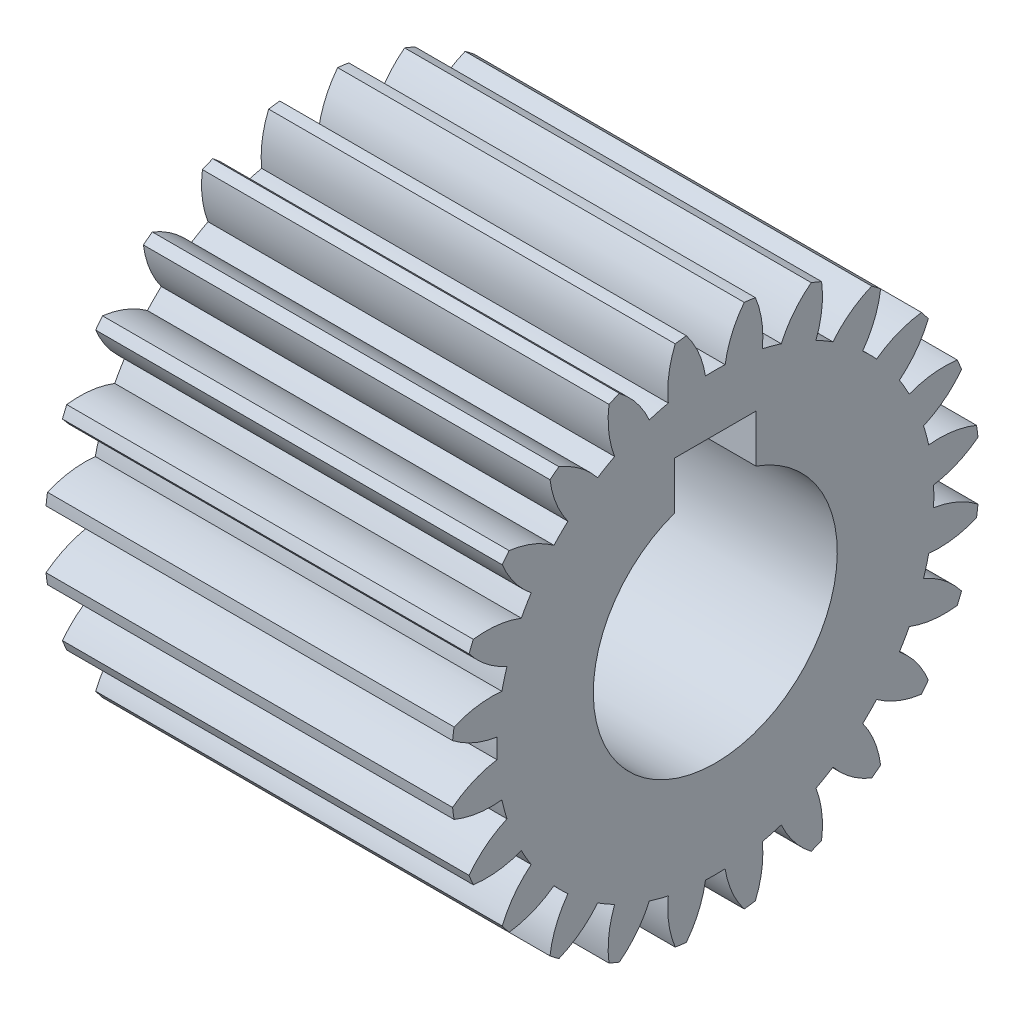
SolidWorks part; units mm, degrees
ref_plane "Plane1" through (0, 0, 0) normal (0, 0, 1) x (1, 0, 0)
ref_plane "Plane2" through (0, 0, 0) normal (0, 1, 0) x (1, 0, 0)
ref_plane "Plane3" through (0, 0, 0) normal (1, 0, 0) x (0, 0, -1)
sketch "HoldingSke" plane through (0, 0, 0) normal (0, 1, 0) x (1, 0, 0)
  line L0 (0, 0) -> (1.8271, -0.8135)
  line L1 (-15, 0) -> (100, 0) construction
  line L2 (0, 0) -> (-2.1039, 2.3779)
  line L3 (0, 0) -> (-11.863, 4.5341)
  line L4 (0, 0) -> (7.8894, 3.5126)
  line L5 (0, 0) -> (-46.8476, -17.4728)
  line L6 (0, 0) -> (-8.2896, -5.593)
  line L7 (-2.1039, 2.3779) -> (8.6586, 51.2059)
  line L8 (-76.2, 54.61) -> (-75.2, 54.61)
  line L9 (-71.009, 38.7566) -> (-53.1078, 45.2721)
  line L10 (-76.2, 71.12) -> (104.1128, 71.12)
  line L11 (0, 0) -> (-10, 0)
  line L12 (-76.2, 101.6) -> (-76.181, 101.6)
  line L13 (24.9733, 27.94) -> (52.9518, 28.4284)
  line L14 (24.9733, 27.94) -> (24.9743, 27.94)
  line L15 (24.9733, 27.94) -> (100.4006, 29.5858)
  line L16 (-63.627, -0.5) -> (-12.827, -0.5)
  circle A0 centre (0, 0) radius 3
  circle A1 centre (0, 0) radius 5.374
  circle A2 centre (0, 0) radius 37.5
  circle A3 centre (0, 0) radius 3
  dimension "MHD" = 10.748
  dimension "Hub_dia" = 75
  dimension "Bore" = 6
  dimension "MBD" = 6
  dimension "Num_teeth" = 24
  dimension "Pitch" = 2
  dimension "Overall_len" = 50
  dimension "Show_teeth" = 24
  dimension "Thickness" = 10
  dimension "OAL" = 50.0001
  dimension "T_dim" = 1
  dimension "Ap" = 20
  dimension "H" = 19.05
  dimension "Pitch_radius" = 180.3128
  dimension "Width" = 10
  dimension "Backlash" = 0.019
  dimension "Addendum_fac" = 1
  dimension "Dedendum_fac" = 1.25
  dimension "Clearance_fac" = 0.25
  dimension "Dedendum_add" = 0.001
  dimension "Module" = 0.5
sketch "BasProSke" plane through (0, 0, 0) normal (0, 1, 0) x (1, 0, 0)
  line L0 (-10, 0) -> (60, 0) construction
  line L1 (0, 0) -> (0, 6.5)
  line L2 (0, 0) -> (10, 0)
  line L3 (10, 0) -> (10, 6.5)
  line L4 (10, 6.5) -> (0, 6.5)
  dimension "Thickness" = 10
  dimension "Diameter" = 13
revolve "Base-Revolve" add sketch "BasProSke" angle 360 about L0
sketch "TooCutSke" plane through (0, 0, 0) normal (1, 0, 0) x (0, 0, -1)
  line L1 (0, 0) -> (0, 107) construction
  line L2 (0, 0) -> (-0.4257, 5.9849) construction
  line L3 (0, 0) -> (-1.5635, 11.876) construction
  line L4 (-0.4257, 5.9849) -> (-0.7818, 5.938) construction
  arc A0 (0.2416, 5.3686) -> (-0.2416, 5.3686) centre (0, 0) ccw
  arc A1 (0.7297, 6.4845) -> (-0.7297, 6.4845) centre (0, 0) ccw
  circle A2 centre (0, 0) radius 6 construction
  circle A3 centre (0, 0) radius 5.6382 construction
  arc A4 (-0.2416, 5.3686) -> (-0.7297, 6.4845) centre (-2.6126, 4.9963) ccw
  arc A5 (0.7297, 6.4845) -> (0.2416, 5.3686) centre (2.6126, 4.9963) ccw
  dimension "Root_dia" = 10.748
  dimension "Overcut_dia" = 13.0508
  dimension "Pitch_dia" = 12
  dimension "Base_dia" = 11.2763
  dimension "Flank_rad" = 2.4
  dimension "Half_ang" = 7.5
  dimension "Half_CT" = 0.3592
extrude "ToothCut" cut sketch "TooCutSke" along normal through all
fillet "Breaks" [suppressed] radius 0.01
fillet "RootFillets" [suppressed] radius 0.126
pattern_circular "TeethCuts" count 24 every 15 about axis through (-10, 0, 0) along (1, 0, 0) of "ToothCut", "RootFillets", "Breaks"
sketch "HubNeaOneSke" plane through (0, 0, 0) normal (-1, 0, 0) x (0, 0, 1)
  circle A0 centre (0, 0) radius 5.374
  dimension "Diameter" = 10.748
extrude "HubNearOne" [suppressed] add sketch "HubNeaOneSke" along normal blind 40.0001
sketch "HubNeaBotSke" plane through (0, 0, 0) normal (-1, 0, 0) x (0, 0, 1)
  circle A0 centre (0, 0) radius 5.374
  dimension "Diameter" = 10.748
extrude "HubNearBoth" [suppressed] add sketch "HubNeaBotSke" along normal blind 20
ref_plane "FarPln" through (10, 0, 0) normal (1, 0, 0) x (0, 0, -1)
sketch "HubFarSke" plane through (10, 0, 0) normal (1, 0, 0) x (0, 0, -1)
  circle A0 centre (0, 0) radius 5.374
  dimension "Diameter" = 10.748
extrude "HubFar" [suppressed] add sketch "HubFarSke" along normal blind 20
sketch "BorSke" plane through (0, 0, 0) normal (1, 0, 0) x (0, 0, -1)
  circle A0 centre (0, 0) radius 3
  dimension "Diameter" = 6
extrude "Bore" cut sketch "BorSke" along normal mid plane 100.0001
sketch "KeySke" plane through (0, 0, 0) normal (1, 0, 0) x (0, 0, -1)
  line L0 (-1, 0) -> (-1, 4)
  line L1 (-1, 4) -> (1, 4)
  line L2 (1, 4) -> (1, 0)
  line L3 (0, 0) -> (0, 34) construction
  line L4 (-1, 0) -> (1, 0)
  dimension "Offset" = 4
  dimension "Width" = 2
extrude "Keyway" cut sketch "KeySke" along normal mid plane 100.0001
pattern_circular "Keyway2" [suppressed] count 2 every 90 about axis through (-10, 0, 0) along (1, 0, 0)
equation "' \"Module@HoldingSke\" = 6.35"
equation "' \"Num_teeth@HoldingSke\" = 12"
equation "' \"Ap@HoldingSke\" =  20"
equation "' \"Ap@HoldingSke\" = 20"
equation "' \"Width@HoldingSke\" = 0.5 * 25.4"
equation "' \"Hub_dia@HoldingSke\"= 1 * 25.4"
equation "' \"Hub_dia@HoldingSke\" = 1 * 25.4"
equation "' \"Overall_len@HoldingSke\" = 1.0 * 25.4"
equation "' \"Bore@HoldingSke\" = 0.75 * 25.4"
equation "' \"T_dim@HoldingSke\" = 0.1 * 25.4"
equation "' \"Width@KeySke\" = 0.25 * 25.4"
equation "' \"Show_teeth@HoldingSke\" = 13"
equation "' \"Backlash@HoldingSke\" = 0.009 * 25.4"
equation "' \"Addendum_fac@HoldingSke\" = 1.0"
equation "' \"Dedendum_fac@HoldingSke\" = 1.25"
equation "' \"Dedendum_add@HoldingSke\" = 0.00005 * 25.4"
equation "' \"Clearance_fac@HoldingSke\" = 0.25"
equation "\"Pitch@HoldingSke\" = 1 / \"Module@HoldingSke\""
equation "\"Overcut_dia@TooCutSke\" = (\"Num_teeth@HoldingSke\" + 2 * \"Addendum_fac@HoldingSke\") / \"Pitch@HoldingSke\" + 0.002 * 25.4"
equation "\"Pitch_dia@TooCutSke\" = \"Num_teeth@HoldingSke\" / \"Pitch@HoldingSke\""
equation "\"Base_dia@TooCutSke\" = \"Num_teeth@HoldingSke\" / \"Pitch@HoldingSke\" * cos((\"Ap@HoldingSke\"  * 3.14159265 / 180))"
equation "\"Root_dia@TooCutSke\" = (\"Num_teeth@HoldingSke\" + 2) / \"Pitch@HoldingSke\" - 2 * (\"Addendum_fac@HoldingSke\" + \"Dedendum_fac@HoldingSke\") / \"Pitch@HoldingSke\" - \"Dedendum_add@HoldingSke\" * 2"
equation "\"Half_ang@TooCutSke\" = 180 / \"Num_teeth@HoldingSke\""
equation "\"Half_CT@TooCutSke\" = \"Num_teeth@HoldingSke\" / \"Pitch@HoldingSke\" * sin((3.14159265 / 2 / \"Num_teeth@HoldingSke\")) / 2 - 7 * \"Backlash@HoldingSke\" / 4"
equation "\"Flank_rad@TooCutSke\" = \"Num_teeth@HoldingSke\" / \"Pitch@HoldingSke\" / 5"
equation "\"Radius@RootFillets\" = \"Clearance_fac@HoldingSke\" / \"Pitch@HoldingSke\" + \"Dedendum_add@HoldingSke\""
equation "\"Break_rad@Breaks\" = 0.02 / \"Pitch@HoldingSke\""
equation "\"Thickness@HoldingSke\" = \"Width@HoldingSke\""
equation "\"OAL@HoldingSke\" = \"Thickness@HoldingSke\""
equation "\"MHD@HoldingSke\" = (\"Num_teeth@HoldingSke\" + 2) / \"Pitch@HoldingSke\" - 2 * (\"Addendum_fac@HoldingSke\" + \"Dedendum_fac@HoldingSke\")  / \"Pitch@HoldingSke\" - \"Dedendum_add@HoldingSke\" * 2"
equation "\"MBD@HoldingSke\" = (\"Num_teeth@HoldingSke\" + 2) / \"Pitch@HoldingSke\" - 2 * (\"Addendum_fac@HoldingSke\" + \"Dedendum_fac@HoldingSke\")  / \"Pitch@HoldingSke\" - \"Dedendum_add@HoldingSke\" * 2 - 0.002 * 25.4"
equation "\"MHD@HoldingSke\" = ((sgn( \"MHD@HoldingSke\" - \"Hub_dia@HoldingSke\" )-1)*( \"MHD@HoldingSke\" - \"Hub_dia@HoldingSke\" ))/-2+ \"Hub_dia@HoldingSke\""
equation "\"MBD@HoldingSke\" = ((sgn( \"MBD@HoldingSke\" - \"Bore@HoldingSke\" )-1)*( \"MBD@HoldingSke\" - \"Bore@HoldingSke\" ))/-2+ \"Bore@HoldingSke\""
equation "\"OAL@HoldingSke\" = ((sgn( \"OAL@HoldingSke\" - \"Overall_len@HoldingSke\" )+1)*( \"OAL@HoldingSke\" - \"Overall_len@HoldingSke\" ))/2 + \"Overall_len@HoldingSke\" + 0.000002 * 25.4"
equation "\"Num_teeth@TeethCuts\" = int( \"Show_teeth@HoldingSke\" ) + 1"
equation "\"Num_teeth@TeethCuts\" = ((sgn( \"Num_teeth@TeethCuts\" - \"Num_teeth@HoldingSke\" )-1)*( \"Num_teeth@TeethCuts\" - \"Num_teeth@HoldingSke\" ))/-2+ \"Num_teeth@HoldingSke\""
equation "\"Num_teeth@TeethCuts\" = ((sgn( \"Num_teeth@TeethCuts\" - 2.0)+1)*( \"Num_teeth@TeethCuts\" - 2.0))/2 +2.0"
equation "\"Angle@TeethCuts\" = 360.0 / \"Num_teeth@HoldingSke\""
equation "\"Diameter@BasProSke\" = (\"Num_teeth@HoldingSke\" + 2 * \"Addendum_fac@HoldingSke\") / \"Pitch@HoldingSke\""
equation "\"Thickness@BasProSke\"  = \"Thickness@HoldingSke\""
equation "' \"Fillet_rad@BasProSke\" =  \"Thickness@HoldingSke\" * 0.05"
equation "' \"Fillet_rad@BasProSke\" = \"Thickness@HoldingSke\" * 0.05"
equation "\"MHD@HoldingSke\" = ((sgn( \"MHD@HoldingSke\" - \"Root_dia@TooCutSke\" )-1)*( \"MHD@HoldingSke\" - \"Root_dia@TooCutSke\" ))/-2+ \"Root_dia@TooCutSke\""
equation "\"Diameter@HubNeaOneSke\" = \"MHD@HoldingSke\""
equation "\"Length@HubNearOne\" = \"OAL@HoldingSke\" - \"Thickness@BasProSke\""
equation "\"Diameter@HubNeaBotSke\" = \"MHD@HoldingSke\""
equation "\"Length@HubNearBoth\" = ( \"OAL@HoldingSke\" - \"Thickness@BasProSke\" ) / 2.0"
equation "\"Thickness@FarPln\" = \"Thickness@BasProSke\""
equation "\"Diameter@HubFarSke\" = \"MHD@HoldingSke\""
equation "\"Length@HubFar\" = ( \"OAL@HoldingSke\" - \"Thickness@BasProSke\" ) / 2.0"
equation "\"Diameter@BorSke\" = \"MBD@HoldingSke\""
equation "\"D1@Bore\" = \"OAL@HoldingSke\" * 2.0"
equation "\"D1@Keyway\" = \"OAL@HoldingSke\" * 2.0"
equation "\"Offset@KeySke\" = \"T_dim@HoldingSke\" + \"MBD@HoldingSke\" / 2.0"
